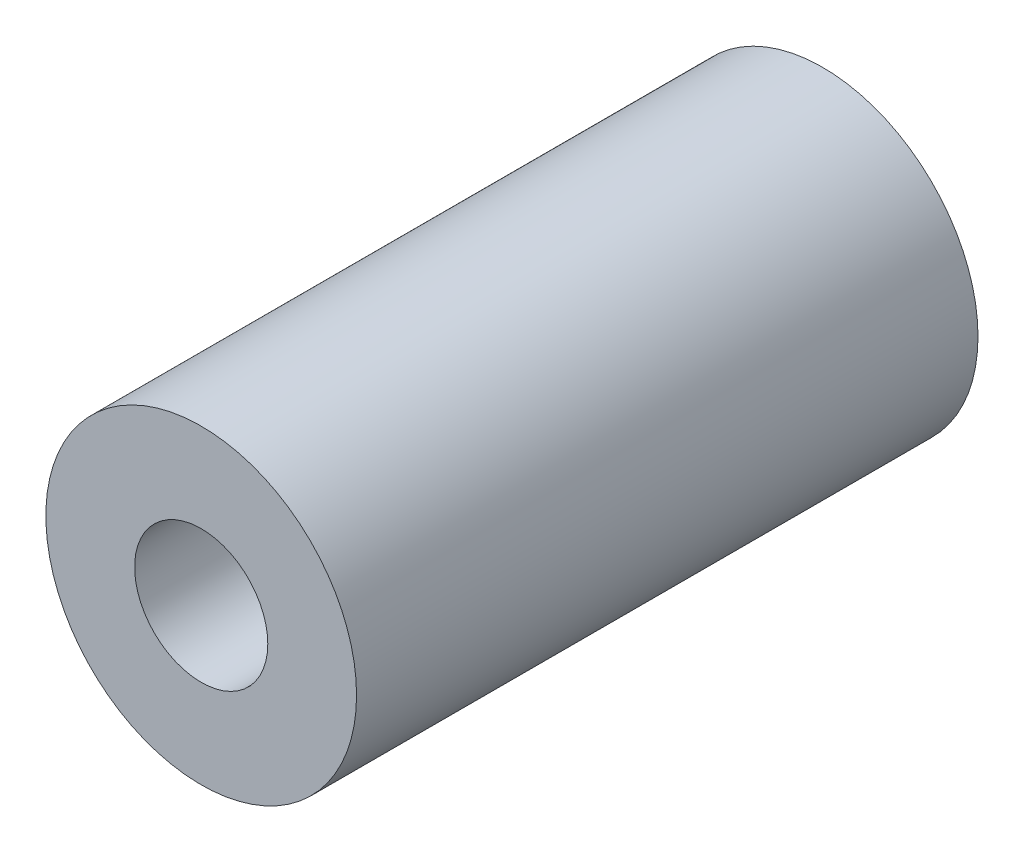
SolidWorks part; units mm, degrees
material "Custom Plastic"
ref_plane "Front Plane" through (0, 0, 0) normal (0, 0, 1) x (1, 0, 0)
ref_plane "Top Plane" through (0, 0, 0) normal (0, 1, 0) x (1, 0, 0)
ref_plane "Right Plane" through (0, 0, 0) normal (1, 0, 0) x (0, 0, -1)
other "Graphic1"
other "Graphic (Closed) -1"
sketch "Sketch1" plane through (0, 0, 0) normal (0, 0, 1) x (1, 0, 0)
  circle A0 centre (80, 72.6314) radius 1.5
extrude "Extrude-Thin1" add sketch "Sketch1" along normal blind 14 thin
